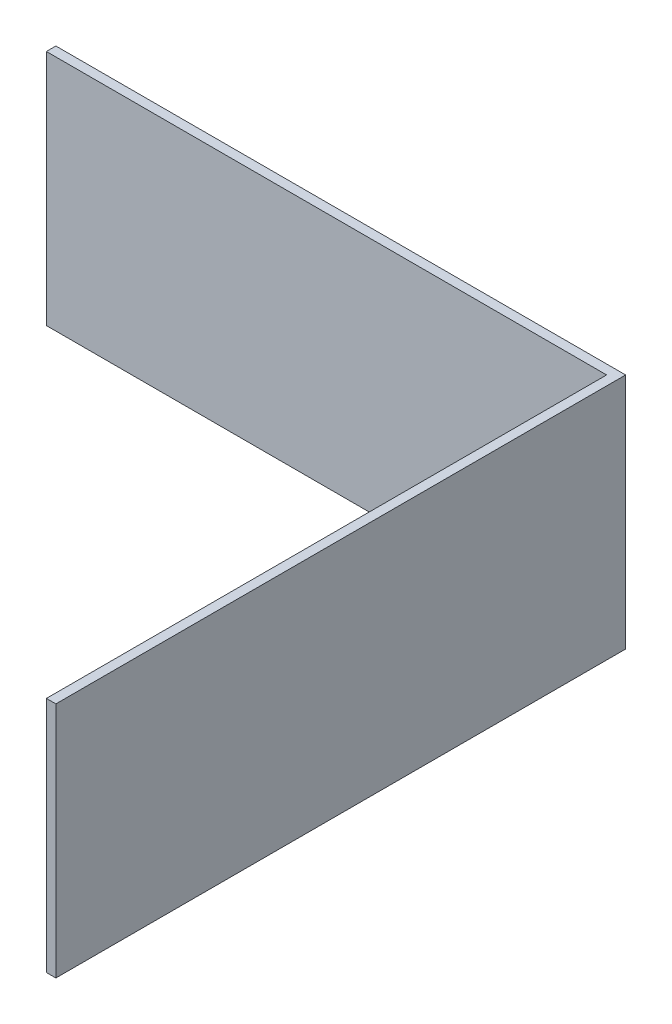
SolidWorks part; units mm, degrees
ref_plane "Alzado" through (0, 0, 0) normal (0, 0, 1) x (1, 0, 0)
ref_plane "Planta" through (0, 0, 0) normal (0, 1, 0) x (1, 0, 0)
ref_plane "Vista lateral" through (0, 0, 0) normal (1, 0, 0) x (0, 0, -1)
sketch "Croquis1" plane through (0, 0, 0) normal (0, 1, 0) x (1, 0, 0)
  line L1 (3000, -3000) -> (-3000, -3000)
  line L2 (3000, -3000) -> (3000, 3000)
  line L3 (3000, 3000) -> (-3000, 3000)
  line L4 (-3000, -3000) -> (-3000, 3000)
  line L5 (3000, -3000) -> (-3000, 3000) construction
  line L6 (3000, 3000) -> (-3000, -3000) construction
  point P0 (0, 0)
  dimension "D1" = 6000
  dimension "D2" = 6000
extrude "Extruir1" add sketch "Croquis1" along normal blind 20
sketch "Croquis2" plane through (0, 20, 0) normal (0, 1, 0) x (1, 0, 0)
  line L0 (3000, 3000) -> (-3000, 3000) construction
  line L1 (3000, 3000) -> (-3000, 3000)
  line L2 (3000, -3000) -> (3000, 3000) construction
  line L3 (3000, -3000) -> (3000, 3000)
  line L4 (3000, -3000) -> (2900, -3000)
  line L5 (-3000, -3000) -> (3000, -3000) construction
  line L6 (-3000, 3000) -> (-3000, 2900)
  line L7 (-3000, 3000) -> (-3000, -3000) construction
  line L8 (-3000, 2900) -> (2900, 2900)
  line L9 (2900, 2900) -> (2900, -3000)
  dimension "D1" = 100
  dimension "D2" = 100
extrude "Extruir2" add sketch "Croquis2" along normal blind 2500 separate body
delete or keep bodies "Sólido-Eliminar1" type delete bodies bodies 101
